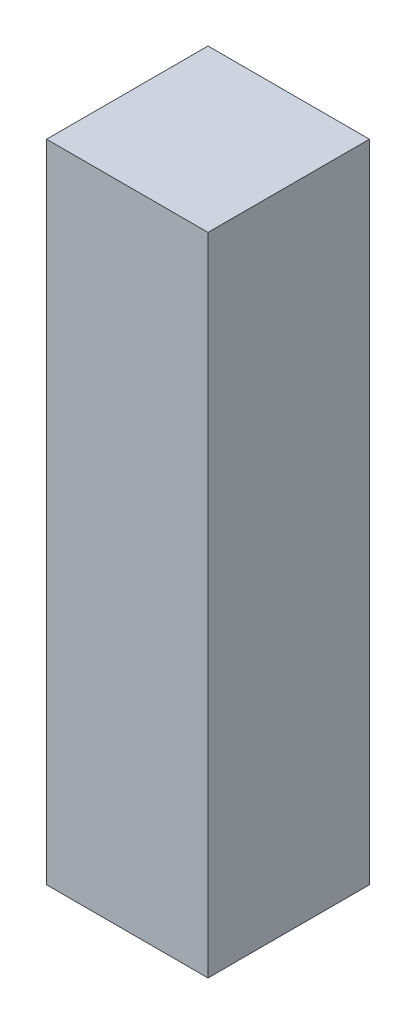
SolidWorks part; units mm, degrees
ref_plane "前视基准面" through (0, 0, 0) normal (0, 0, 1) x (1, 0, 0)
ref_plane "上视基准面" through (0, 0, 0) normal (0, 1, 0) x (1, 0, 0)
ref_plane "右视基准面" through (0, 0, 0) normal (1, 0, 0) x (0, 0, -1)
sketch "草图1" plane through (0, 0, 0) normal (0, 1, 0) x (1, 0, 0)
  line L1 (10, -10) -> (-10, -10)
  line L2 (10, -10) -> (10, 10)
  line L3 (10, 10) -> (-10, 10)
  line L4 (-10, -10) -> (-10, 10)
  line L5 (10, -10) -> (-10, 10) construction
  line L6 (10, 10) -> (-10, -10) construction
  point P0 (0, 0)
  dimension "D1" = 20
  dimension "D2" = 20
extrude "凸台-拉伸1" add sketch "草图1" along normal blind 80
